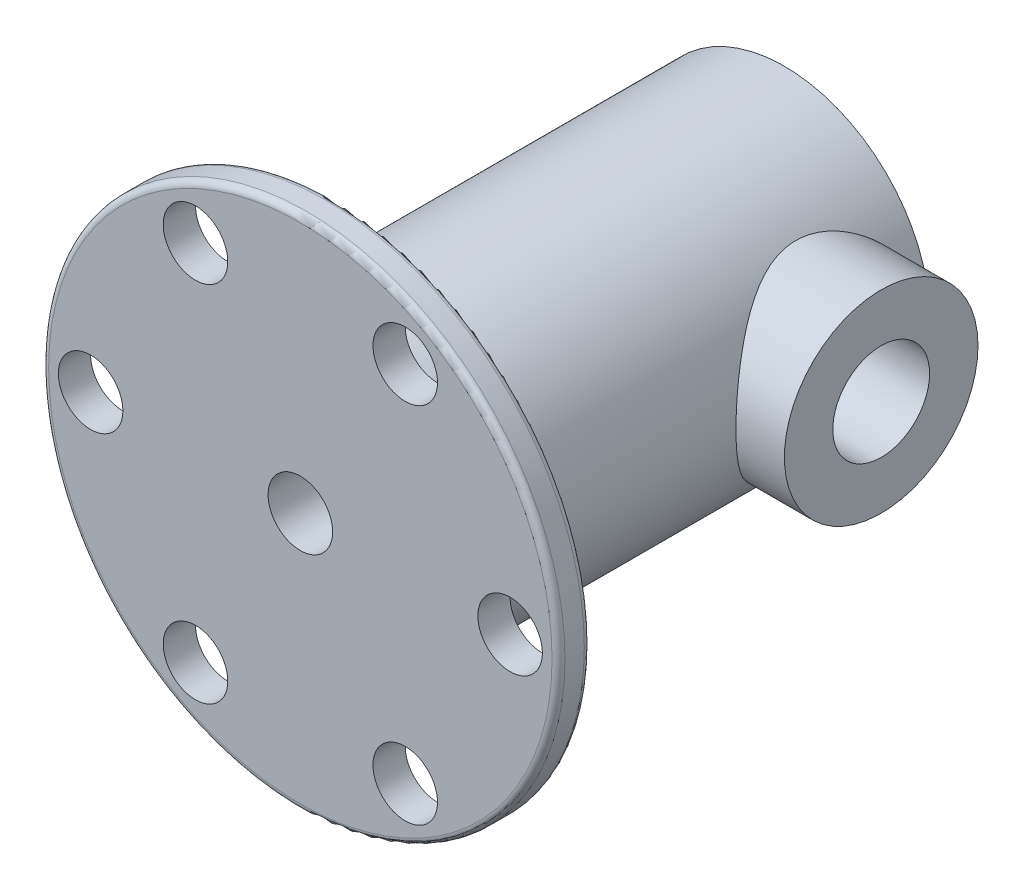
SolidWorks part; units mm, degrees
ref_plane "前视基准面" through (0, 0, 0) normal (0, 0, 1) x (1, 0, 0)
ref_plane "上视基准面" through (0, 0, 0) normal (0, 1, 0) x (1, 0, 0)
ref_plane "右视基准面" through (0, 0, 0) normal (1, 0, 0) x (0, 0, -1)
other "Configuration Table"
sketch "草图1" plane through (0, 0, 0) normal (0, 0, 1) x (1, 0, 0)
  line L0 (0, 0) -> (-80, 0)
  circle A0 centre (0, 0) radius 80
  dimension "D1" = 160
extrude "凸台-拉伸1" add sketch "草图1" along normal blind 10
sketch "草图2" plane through (0, 0, 0) normal (0, 0, 1) x (1, 0, 0)
  line L0 (0, 0) -> (-80, 0)
  circle A0 centre (0, 0) radius 80 construction
  circle A1 centre (-65, 0) radius 10
  circle A2 centre (-32.5, 56.2917) radius 10
  circle A3 centre (32.5, 56.2917) radius 10
  circle A4 centre (65, 0) radius 10
  circle A5 centre (32.5, -56.2917) radius 10
  circle A6 centre (-32.5, -56.2917) radius 10
  point P21 (0, 0)
  dimension "D1" = 20
  dimension "D2" = 15
  dimension "D3" = 6
extrude "切除-拉伸1" cut sketch "草图2" along normal blind 10 contours A3 | A6 | A1 | A2 | A4 | A5
sketch "草图3" plane through (0, 0, 0) normal (0, 0, 1) x (1, 0, 0)
  circle A0 centre (0, 0) radius 45 construction
  circle A1 centre (0, 0) radius 29.5 construction
  circle A2 centre (0, 0) radius 45
  dimension "D1" = 90
  dimension "D2" = 59
extrude "凸台-拉伸2" add sketch "草图3" against normal blind 140
sketch "草图6" plane through (0, 0, 0) normal (0, 0, 1) x (1, 0, 0)
  circle A0 centre (0, 0) radius 10
  dimension "D1" = 20
extrude "切除-拉伸3" cut sketch "草图6" against normal through all
sketch "草图7" plane through (0, 0, 0) normal (1, 0, 0) x (0, 0, -1)
  circle A0 centre (110, 0) radius 30
  circle A1 centre (110, 0) radius 15
  dimension "D2" = 30
extrude "凸台-拉伸3" add sketch "草图7" along normal blind 60
sketch "草图8" plane through (0, 0, 0) normal (1, 0, 0) x (0, 0, -1)
  line L0 (140, -10) -> (140, 10) construction
  circle A1 centre (110, 0) radius 15
extrude "切除-拉伸4" cut sketch "草图8" against normal mid plane 90
sketch "草图9" plane through (0, 0, 10) normal (0, 0, 1) x (1, 0, 0)
  circle A0 centre (0, 0) radius 10
  dimension "D1" = 20
extrude "切除-拉伸5" cut sketch "草图9" against normal blind 200
fillet "圆角1" radius 2 2 edges at (80, 0, 0) (80, 0, 10)
